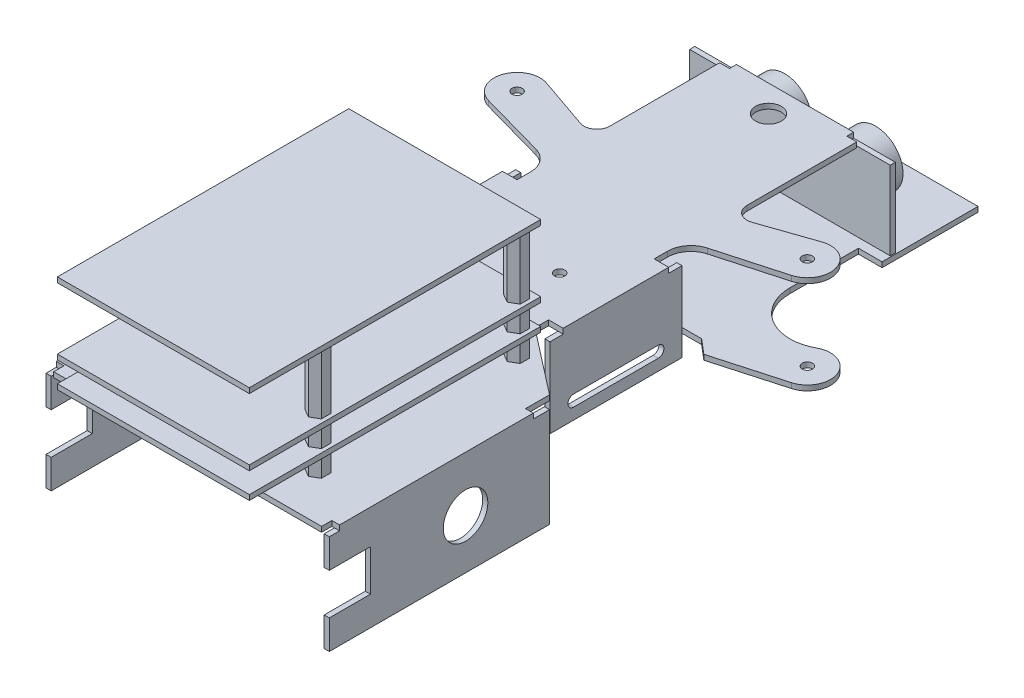
SolidWorks part; units mm, degrees
ref_plane "Front Plane" through (0, 0, 0) normal (0, 0, 1) x (1, 0, 0)
ref_plane "Top Plane" through (0, 0, 0) normal (0, 1, 0) x (1, 0, 0)
ref_plane "Right Plane" through (0, 0, 0) normal (1, 0, 0) x (0, 0, -1)
sketch "Sketch2" plane through (0, 0, 0) normal (0, 1, 0) x (1, 0, 0)
  line L0 (-20, 141.95) -> (20, 141.95)
  line L2 (-39.075, -33.25) -> (-39.075, 33.25)
  line L5 (39.075, -33.25) -> (-39.075, -33.25)
  line L6 (41.325, -30.25) -> (41.325, 26.25)
  line L7 (39.075, 26.25) -> (41.325, 26.25)
  line L8 (-20, 141.95) -> (-20, 48.05)
  line L9 (-20, 48.05) -> (-39.075, 33.25)
  line L10 (0, -97.46) -> (0, 97.46) construction
  line L11 (-40.1468, 111.5803) -> (-20, 104.6235)
  line L12 (-20, 82.85) -> (-24.25, 82.85)
  line L13 (-20, 82.85) -> (-20, 52.05)
  line L14 (-20, 52.05) -> (-24.25, 52.05)
  line L15 (-24.25, 82.85) -> (-24.25, 52.05)
  line L16 (-44.1645, 98.6984) -> (-20, 91.9546)
  line L17 (-17.1, 141.95) -> (17.1, 141.95)
  line L18 (-39.075, -30.25) -> (-41.325, -30.25)
  line L19 (-39.075, -30.25) -> (-39.075, 26.25)
  line L20 (-39.075, 26.25) -> (-41.325, 26.25)
  line L21 (-41.325, -30.25) -> (-41.325, 26.25)
  line L22 (-17.1, 141.95) -> (-17.1, 143.95)
  line L23 (-17.1, 143.95) -> (17.1, 143.95)
  line L24 (17.1, 141.95) -> (17.1, 143.95)
  line L25 (-17.1, 141.95) -> (17.1, 143.95) construction
  line L26 (-17.1, 143.95) -> (17.1, 141.95) construction
  line L27 (39.075, -30.25) -> (39.075, 26.25)
  line L28 (39.075, -30.25) -> (41.325, -30.25)
  line L29 (44.1645, 98.6984) -> (20, 91.9546)
  line L30 (24.25, 82.85) -> (24.25, 52.05)
  line L31 (20, 52.05) -> (24.25, 52.05)
  line L32 (20, 82.85) -> (20, 52.05)
  line L33 (20, 82.85) -> (24.25, 82.85)
  line L34 (40.1468, 111.5803) -> (20, 104.6235)
  line L35 (20, 48.05) -> (39.075, 33.25)
  line L36 (20, 141.95) -> (20, 48.05)
  line L37 (39.075, -33.25) -> (39.075, 33.25)
  circle A0 centre (-42.35, 105.2) radius 6.75
  arc A1 (-20, 109.9132) -> (-25, 106.35) centre (-23.7696, 109.9132) cw
  arc A2 (-25, 93.35) -> (-20, 86.7635) centre (-26.8382, 86.7635) cw
  arc A3 (25, 93.35) -> (20, 86.7635) centre (26.8382, 86.7635) ccw
  arc A4 (20, 109.9132) -> (25, 106.35) centre (23.7696, 109.9132) ccw
  circle A5 centre (42.35, 105.2) radius 6.75
  point P0 (-39.075, 0)
  point P5 (0, -33.25)
  point P9 (0, 141.95)
  point P25 (0, 142.95)
  point P63 (39.075, 0)
  dimension "D9" = 13.5
  dimension "D10" = 29.1
  dimension "D13" = 30
  dimension "D2" = 66.5
  dimension "D3" = 78.15
  dimension "D4" = 40
  dimension "D5" = 93.9
  dimension "D6" = 30.8
  dimension "D7" = 4.25
  dimension "D8" = 4
  dimension "D11" = 13
  dimension "D12" = 35.6
  dimension "D14" = 5
  dimension "D15" = 56.5
  dimension "D16" = 2.25
  dimension "D17" = 3
  dimension "D18" = 34.2
  dimension "D19" = 2
  dimension "D20" = 175.2
extrude "Boss-Extrude1" add sketch "Sketch2" along normal blind 1.5 contours L5 L37 L27 L35 L36 L32 L0 L8 L9 L2 | L21 L18 L2 L20 | L12 L15 L14 L8 | L33 L32 L31 L30 | L29 A5 L34 L36 | A4 L36 L34 | A3 L29 L36 | A0 L16 L8 L11 | A0 | L8 A1 L11 | L16 A2 L8 | L0 L24 L23 L22 | L27 L28 L6 L7 | A5
sketch "Sketch4" plane through (0, 0, 0) normal (0, -1, 0) x (1, 0, 0)
  line L0 (41.325, 30.25) -> (41.325, -26.25) construction
  line L1 (41.325, 33.25) -> (39.825, 33.25)
  line L2 (41.325, 33.25) -> (41.325, -31)
  line L3 (41.325, -31) -> (39.825, -31)
  line L4 (39.825, 33.25) -> (39.825, -31)
  line L5 (39.075, 33.25) -> (-39.075, 33.25) construction
  dimension "D1" = 1.5
  dimension "D2" = 64.25
extrude "Boss-Extrude2" add sketch "Sketch4" along normal blind 29
sketch "Sketch5" plane through (41.325, 0, 0) normal (1, 0, 0) x (0, 0, -1)
  line L0 (31, -29) -> (-33.25, -29) construction
  line L1 (-33.25, -20.5) -> (-21.25, -20.5)
  line L2 (-33.25, -20.5) -> (-33.25, -8.5)
  line L3 (-33.25, -8.5) -> (-21.25, -8.5)
  line L4 (-21.25, -20.5) -> (-21.25, -8.5)
  line L5 (-33.25, -20.5) -> (-21.25, -8.5) construction
  line L6 (-33.25, -8.5) -> (-21.25, -20.5) construction
  line L7 (-33.25, -29) -> (-33.25, 0) construction
  line L8 (31, -29) -> (31, 0) construction
  circle A0 centre (6.5, -14.5) radius 6.5
  point P0 (-27.25, -14.5)
  dimension "D4" = 13
  dimension "D5" = 8
  dimension "D1" = 12
  dimension "D2" = 12
  dimension "D3" = 8.5
  dimension "D6" = 18
extrude "Cut-Extrude1" cut sketch "Sketch5" against normal up to surface (1.5 mm away) up to face at (39.825, -9.6667, 1.4167)
mirror "Mirror1" about plane through (0, 0, 0) normal (1, 0, 0) of "Cut-Extrude1", "Boss-Extrude2"
sketch "Sketch6" plane through (0, 0, 0) normal (0, -1, 0) x (1, 0, 0)
  line L0 (-24.25, -82.85) -> (-24.25, -52.05) construction
  line L1 (-24.25, -86.7) -> (-22.75, -86.7)
  line L2 (-24.25, -86.7) -> (-24.25, -48.2)
  line L3 (-24.25, -48.2) -> (-22.75, -48.2)
  line L4 (-22.75, -86.7) -> (-22.75, -48.2)
  line L5 (-24.25, -86.7) -> (-22.75, -48.2) construction
  line L6 (-24.25, -48.2) -> (-22.75, -86.7) construction
  point P0 (-23.5, -67.45)
  point P8 (-24.25, -67.45)
  dimension "D1" = 38.5
  dimension "D2" = 1.5
extrude "Boss-Extrude3" add sketch "Sketch6" along normal blind 23.25
sketch "Sketch7" plane through (-24.25, 0, 0) normal (-1, 0, 0) x (0, 0, 1)
  line L0 (-79.8, -18.3) -> (-55.1, -18.3) construction
  line L1 (-79.8, -16.65) -> (-55.1, -16.65)
  line L2 (-79.8, -19.95) -> (-55.1, -19.95)
  line L3 (-48.2, -23.25) -> (-86.7, -23.25) construction
  arc A0 (-79.8, -16.65) -> (-79.8, -19.95) centre (-79.8, -18.3) ccw
  arc A1 (-55.1, -19.95) -> (-55.1, -16.65) centre (-55.1, -18.3) ccw
  point P2 (-67.45, -18.3)
  point P7 (-67.45, -23.25)
  dimension "D2" = 28
  dimension "D1" = 3.3
  dimension "D3" = 3.3
extrude "Cut-Extrude2" cut sketch "Sketch7" against normal up to surface (1.5 mm away) up to face at (-22.75, -7.75, -67.45)
mirror "Mirror2" about plane through (0, 0, 0) normal (1, 0, 0) of "Cut-Extrude2", "Boss-Extrude3"
sketch "Sketch8" plane through (0, 0, 0) normal (0, -1, 0) x (1, 0, 0)
  line L0 (0, -16.775) -> (0, 16.775) construction
  line L1 (-29.25, -143.95) -> (29.25, -143.95)
  line L2 (-29.25, -143.95) -> (-29.25, -142.45)
  line L3 (-29.25, -142.45) -> (29.25, -142.45)
  line L4 (29.25, -143.95) -> (29.25, -142.45)
  line L5 (-29.25, -143.95) -> (29.25, -142.45) construction
  line L6 (-29.25, -142.45) -> (29.25, -143.95) construction
  line L7 (-17.1, -143.95) -> (17.1, -143.95) construction
  point P0 (0, -143.2)
  dimension "D1" = 1.5
  dimension "D2" = 58.5
extrude "Boss-Extrude4" add sketch "Sketch8" along normal blind 22.9
sketch "Sketch9" plane through (0, 0, -143.95) normal (0, 0, -1) x (-1, 0, 0)
  line L1 (29.25, -22.9) -> (29.25, 0) construction
  line L3 (29.25, -22.9) -> (-29.25, -22.9) construction
  circle A0 centre (13.3, -11.95) radius 7.95
  dimension "D1" = 15.9
  dimension "D2" = 8
  dimension "D3" = 3
extrude "Boss-Extrude5" add sketch "Sketch9" along normal blind 10.25
mirror "Mirror3" about plane through (0, 0, 0) normal (1, 0, 0) of "Boss-Extrude5"
ref_plane "Plane1" through (0, -25.6, 0) normal (0, -1, 0) x (-1, 0, 0)
sketch "Sketch11" plane through (0, -25.6, 0) normal (0, -1, 0) x (-1, 0, 0)
  line L0 (-20, 96.693) -> (20, 96.693)
  line L1 (-20, 122.45) -> (-20, 142.45)
  line L2 (0, 16.775) -> (0, -16.775) construction
  line L3 (-29.25, 142.45) -> (29.25, 142.45) construction
  line L4 (-26.875, 142.45) -> (26.875, 142.45)
  line L5 (-26.875, 142.45) -> (-26.875, 170.45)
  line L6 (-26.875, 170.45) -> (26.875, 170.45)
  line L7 (26.875, 142.45) -> (26.875, 170.45)
  line L8 (-26.875, 142.45) -> (26.875, 170.45) construction
  line L9 (-26.875, 170.45) -> (26.875, 142.45) construction
  line L10 (-44.1789, 98.7025) -> (-24.25, 93.093)
  line L11 (-24.25, 93.093) -> (-20, 96.693)
  line L13 (-24.25, 48.2) -> (-24.25, 86.7) construction
  line L14 (24.25, 93.093) -> (20, 96.693)
  line L15 (44.1789, 98.7025) -> (24.25, 93.093)
  line L16 (20, 122.45) -> (20, 142.45)
  circle A0 centre (-42.35, 105.2) radius 6.75
  arc A1 (-40.1468, 111.5803) -> (-44.1645, 98.6984) centre (-42.35, 105.2) ccw construction
  arc A2 (-20, 86.7635) -> (-25, 93.35) centre (-26.8382, 86.7635) ccw construction
  arc A3 (-20, 122.45) -> (-39.1103, 111.1217) centre (-32.9128, 122.45) cw
  arc A4 (20, 122.45) -> (39.1103, 111.1217) centre (32.9128, 122.45) ccw
  circle A5 centre (42.35, 105.2) radius 6.75
  point P9 (0, 156.45)
  point P40 (0, 96.693)
  dimension "D1" = 13.5
  dimension "D2" = 20
  dimension "D3" = 28
  dimension "D4" = 53.75
  dimension "D5" = 3.6
  dimension "D6" = 20
extrude "Boss-Extrude6" add sketch "Sketch11" along normal blind 1.5 separate body contours L4 L7 L6 L5 | L15 A5 A4 L16 L4 L1 A3 A0 L10 L11 L0 L14 | A0 | A5
sketch "Sketch12" plane through (0, 1.5, 0) normal (0, 1, 0) x (1, 0, 0)
  line L0 (-24.5, -19.75) -> (24.5, -19.75) construction
  line L1 (0, -16.775) -> (0, 16.775) construction
  line L2 (39.075, -33.25) -> (-39.075, -33.25) construction
  line L3 (-9.8, 65.4908) -> (9.8, 65.4908) construction
  circle A0 centre (-24.5, -19.75) radius 1.375
  circle A1 centre (24.5, -19.75) radius 1.375
  circle A2 centre (24.5, 38.25) radius 1.375
  circle A3 centre (-24.5, 38.25) radius 1.375
  circle A4 centre (-42.35, 105.2) radius 1.5
  circle A5 centre (42.35, 105.2) radius 1.5
  arc A6 (-40.1468, 111.5803) -> (-44.1645, 98.6984) centre (-42.35, 105.2) ccw construction
  arc A7 (44.1645, 98.6984) -> (40.1468, 111.5803) centre (42.35, 105.2) ccw construction
  circle A8 centre (-9.8, 65.4908) radius 1.5
  circle A9 centre (9.8, 65.4908) radius 1.5
  point P2 (0, -19.75)
  point P27 (0, 65.4908)
  dimension "D5" = 2.75
  dimension "D7" = 3
  dimension "D8" = 16.6
  dimension "D3" = 58
  dimension "D4" = 49
  dimension "D6" = 13.5
  dimension "D1" = 2
  dimension "D2" = 2
extrude "Cut-Extrude3" cut sketch "Sketch12" against normal through all
sketch "Sketch13" plane through (0, 1.5, 0) normal (0, 1, 0) x (1, 0, 0)
  line L0 (24.5, 41.0213) -> (22.1, 39.6356)
  line L1 (-24.5, 41.0213) -> (-26.9, 39.6356)
  line L2 (-26.9, 39.6356) -> (-26.9, 36.8644)
  line L3 (-26.9, 36.8644) -> (-24.5, 35.4787)
  line L4 (-24.5, 35.4787) -> (-22.1, 36.8644)
  line L5 (-22.1, 36.8644) -> (-22.1, 39.6356)
  line L6 (-22.1, 39.6356) -> (-24.5, 41.0213)
  line L7 (22.1, 39.6356) -> (22.1, 36.8644)
  line L8 (22.1, 36.8644) -> (24.5, 35.4787)
  line L9 (24.5, 35.4787) -> (26.9, 36.8644)
  line L10 (26.9, 36.8644) -> (26.9, 39.6356)
  line L11 (26.9, 39.6356) -> (24.5, 41.0213)
  line L12 (24.5, -16.9787) -> (22.1, -18.3644)
  line L13 (22.1, -18.3644) -> (22.1, -21.1356)
  line L14 (22.1, -21.1356) -> (24.5, -22.5213)
  line L15 (24.5, -22.5213) -> (26.9, -21.1356)
  line L16 (26.9, -21.1356) -> (26.9, -18.3644)
  line L17 (26.9, -18.3644) -> (24.5, -16.9787)
  line L18 (-24.5, -16.9787) -> (-26.9, -18.3644)
  line L19 (-26.9, -18.3644) -> (-26.9, -21.1356)
  line L20 (-26.9, -21.1356) -> (-24.5, -22.5213)
  line L21 (-24.5, -22.5213) -> (-22.1, -21.1356)
  line L22 (-22.1, -21.1356) -> (-22.1, -18.3644)
  line L23 (-22.1, -18.3644) -> (-24.5, -16.9787)
  circle A0 centre (-24.5, 38.25) radius 2.4 construction
  circle A1 centre (24.5, 38.25) radius 2.4 construction
  circle A2 centre (24.5, -19.75) radius 2.4 construction
  circle A3 centre (-24.5, -19.75) radius 2.4 construction
  circle A4 centre (24.5, -19.75) radius 1.375 construction
  circle A5 centre (24.5, 38.25) radius 1.375 construction
  dimension "D1" = 4.8
  dimension "D2" = 2
  dimension "D3" = 2
extrude "Boss-Extrude7" add sketch "Sketch13" along normal blind 6
sketch "Sketch14" plane through (0, 7.5, 0) normal (0, 1, 0) x (1, 0, 0)
  line L0 (0, -20.075) -> (0, 20.075) construction
  line L1 (-28, -43.25) -> (28, -43.25)
  line L2 (-28, -43.25) -> (-28, 41.75)
  line L3 (-28, 41.75) -> (28, 41.75)
  line L4 (28, -43.25) -> (28, 41.75)
  line L5 (-28, -43.25) -> (28, 41.75) construction
  line L6 (-28, 41.75) -> (28, -43.25) construction
  line L7 (-22.1, 36.8644) -> (-22.1, 39.6356) construction
  point P0 (0, -0.75)
  point P7 (-24.5, 38.25)
  point P8 (-22.1, 38.25)
  dimension "D1" = 85
  dimension "D2" = 56
  dimension "D3" = 3.5
extrude "Boss-Extrude8" add sketch "Sketch14" along normal blind 1.5
pattern_linear "LPattern1" count 2 spacing 7.5 along (0, 1, 0) of "Boss-Extrude7"
pattern_linear "LPattern2" count 2 spacing 7.5 along (0, 1, 0) of "Boss-Extrude8"
sketch "Sketch16" plane through (0, 16.5, 0) normal (0, 1, 0) x (1, 0, 0)
  line L0 (24.5, 41.0213) -> (22.1, 39.6356)
  line L1 (-24.5, 41.0213) -> (-26.9, 39.6356)
  line L2 (-26.9, 39.6356) -> (-26.9, 36.8644)
  line L3 (-26.9, 36.8644) -> (-24.5, 35.4787)
  line L4 (-24.5, 35.4787) -> (-22.1, 36.8644)
  line L5 (-22.1, 36.8644) -> (-22.1, 39.6356)
  line L6 (-22.1, 39.6356) -> (-24.5, 41.0213)
  line L7 (22.1, 39.6356) -> (22.1, 36.8644)
  line L8 (22.1, 36.8644) -> (24.5, 35.4787)
  line L9 (24.5, 35.4787) -> (26.9, 36.8644)
  line L10 (26.9, 36.8644) -> (26.9, 39.6356)
  line L11 (26.9, 39.6356) -> (24.5, 41.0213)
  line L12 (24.5, -16.9787) -> (22.1, -18.3644)
  line L13 (22.1, -18.3644) -> (22.1, -21.1356)
  line L14 (22.1, -21.1356) -> (24.5, -22.5213)
  line L15 (24.5, -22.5213) -> (26.9, -21.1356)
  line L16 (26.9, -21.1356) -> (26.9, -18.3644)
  line L17 (26.9, -18.3644) -> (24.5, -16.9787)
  line L18 (-24.5, -16.9787) -> (-26.9, -18.3644)
  line L19 (-26.9, -18.3644) -> (-26.9, -21.1356)
  line L20 (-26.9, -21.1356) -> (-24.5, -22.5213)
  line L21 (-24.5, -22.5213) -> (-22.1, -21.1356)
  line L22 (-22.1, -21.1356) -> (-22.1, -18.3644)
  line L23 (-22.1, -18.3644) -> (-24.5, -16.9787)
  line L24 (-26.9, 39.6356) -> (-26.9, 36.8644) construction
  line L25 (-24.5, 41.0213) -> (-26.9, 39.6356) construction
  line L26 (26.9, 39.6356) -> (24.5, 41.0213) construction
  line L29 (26.9, -18.3644) -> (24.5, -16.9787) construction
  line L30 (24.5, -22.5213) -> (26.9, -21.1356) construction
  circle A0 centre (-24.5, 38.25) radius 2.4 construction
  circle A1 centre (24.5, 38.25) radius 2.4 construction
  circle A2 centre (24.5, -19.75) radius 2.4 construction
  circle A3 centre (-24.5, -19.75) radius 2.4 construction
  dimension "D1" = 4.8
  dimension "D2" = 2
  dimension "D3" = 2
extrude "Boss-Extrude10" add sketch "Sketch16" along normal blind 18
pattern_linear "LPattern3" count 2 spacing 27 along (0, 1, 0) of "Boss-Extrude8"
sketch "Sketch17" plane through (0, 1.5, 0) normal (0, 1, 0) x (1, 0, 0)
  line L0 (0, -35.75) -> (0, 35.75) construction
  line L2 (-17.1, 143.95) -> (17.1, 143.95) construction
  circle A0 centre (0, 136.2) radius 3.75
  dimension "D1" = 7.5
  dimension "D2" = 4
extrude "Cut-Extrude4" cut sketch "Sketch17" against normal up to surface (1.5 mm away) up to face at (-24.5, 0, 21.125)
